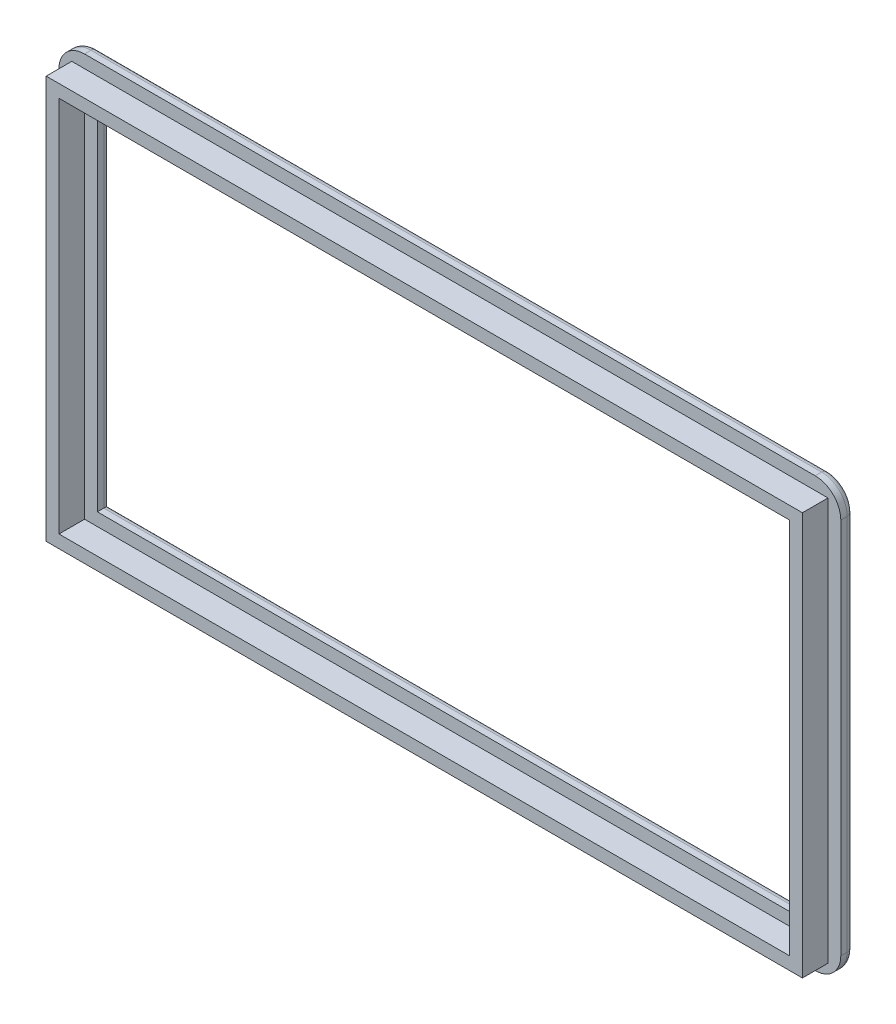
SolidWorks part; units mm, degrees
ref_plane "Front Plane" through (0, 0, 0) normal (0, 0, 1) x (1, 0, 0)
ref_plane "Top Plane" through (0, 0, 0) normal (0, 1, 0) x (1, 0, 0)
ref_plane "Right Plane" through (0, 0, 0) normal (1, 0, 0) x (0, 0, -1)
sketch "Sketch1" plane through (0, 0, 0) normal (0, 0, 1) x (1, 0, 0)
  line L1 (-27.55, 13.745) -> (27.55, 13.745)
  line L2 (-27.55, 13.745) -> (-27.55, -13.745)
  line L3 (-27.55, -13.745) -> (27.55, -13.745)
  line L4 (27.55, 13.745) -> (27.55, -13.745)
  line L5 (-27.55, 13.745) -> (27.55, -13.745) construction
  line L6 (-27.55, -13.745) -> (27.55, 13.745) construction
  line L7 (-28.55, 16.745) -> (28.55, 16.745)
  line L8 (-30.55, 14.745) -> (-30.55, -14.745)
  line L9 (-28.55, -16.745) -> (28.55, -16.745)
  line L10 (30.55, 14.745) -> (30.55, -14.745)
  line L11 (-30.55, 16.745) -> (30.55, -16.745) construction
  line L12 (-30.55, -16.745) -> (30.55, 16.745) construction
  arc A0 (28.55, -16.745) -> (30.55, -14.745) centre (28.55, -14.745) ccw
  arc A1 (-30.55, -14.745) -> (-28.55, -16.745) centre (-28.55, -14.745) ccw
  arc A2 (-28.55, 16.745) -> (-30.55, 14.745) centre (-28.55, 14.745) ccw
  arc A3 (28.55, 16.745) -> (30.55, 14.745) centre (28.55, 14.745) cw
  point P0 (0, 0)
  point P5 (0, 0)
  dimension "D5" = 2
  dimension "D1" = 55.1
  dimension "D2" = 27.49
  dimension "D3" = 3
  dimension "D4" = 3
extrude "Boss-Extrude1" add sketch "Sketch1" along normal blind 1
fillet "Fillet2" radius 0.5 12 edges at (0, -13.745, 0) (-27.55, 0, 0) (0, 13.745, 0) (27.55, 0, 0) (30.55, 0, 0) (0, 16.745, 0) (-30.55, 0, 0) (0, -16.745, 0) (29.9642, 16.1592, 0) (-29.9642, 16.1592, 0) (-29.9642, -16.1592, 0) (29.9642, -16.1592, 0)
sketch "Sketch3" plane through (0, 0, 1) normal (0, 0, 1) x (1, 0, 0)
  line L12 (29.55, 15.745) -> (-29.55, 15.745)
  line L13 (-29.55, 15.745) -> (-29.55, -15.745)
  line L14 (-29.55, -15.745) -> (29.55, -15.745)
  line L15 (29.55, -15.745) -> (29.55, 15.745)
  line L16 (28.55, -14.745) -> (28.55, 14.745)
  line L17 (-28.55, -14.745) -> (28.55, -14.745)
  line L18 (-28.55, 14.745) -> (-28.55, -14.745)
  line L19 (28.55, 14.745) -> (-28.55, 14.745)
  line L20 (28.55, -14.745) -> (28.55, 14.745)
  line L21 (-28.55, -14.745) -> (28.55, -14.745)
  line L22 (-28.55, 14.745) -> (-28.55, -14.745)
  line L23 (28.55, 14.745) -> (-28.55, 14.745)
  dimension "D1" = 1
  dimension "D2" = 1
  dimension "D3" = 31.49
  dimension "D4" = 59.1
extrude "Boss-Extrude2" add sketch "Sketch3" along normal blind 2
